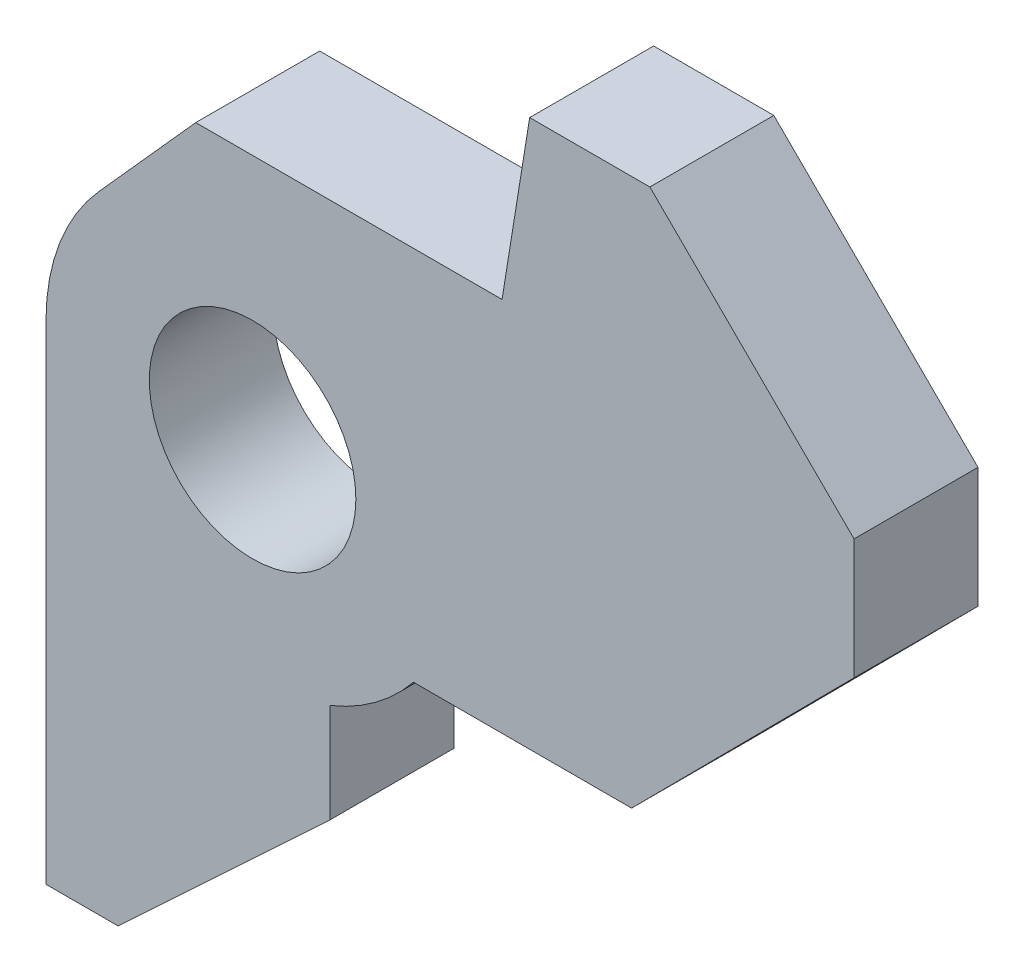
SolidWorks part; units mm, degrees
ref_plane "정면" through (0, 0, 0) normal (0, 0, 1) x (1, 0, 0)
ref_plane "윗면" through (0, 0, 0) normal (0, 1, 0) x (1, 0, 0)
ref_plane "우측면" through (0, 0, 0) normal (1, 0, 0) x (0, 0, -1)
sketch "스케치1" plane through (0, 0, 0) normal (0, 0, 1) x (1, 0, 0)
  line L1 (6.0379, 5.9574) -> (6.7063, 10.1037)
  line L2 (6.7063, 10.1037) -> (9.6154, 10.1037)
  line L3 (9.6154, 10.1037) -> (14.5571, 5.198)
  line L4 (14.5571, 5.198) -> (14.5571, 2.2863)
  line L5 (14.5571, 2.2863) -> (9.173, -3.1374)
  line L6 (9.173, -3.1374) -> (3.8932, -3.1374)
  line L7 (1.8761, -4.6347) -> (1.8761, -7.0314)
  line L8 (-3.2535, -11.8209) -> (-5, -11.8209)
  line L9 (-5, -11.8209) -> (-5, 0)
  line L10 (-3.2535, -11.8209) -> (1.8761, -7.0314)
  line L11 (6.0379, 5.9574) -> (-1.3764, 5.9574)
  line L12 (-1.3764, 5.9574) -> (-3.7244, 3.336)
  circle A0 centre (0, 0) radius 2.5
  circle A1 centre (0, 0) radius 5
  dimension "D1" = 5
  dimension "D2" = 10
extrude "보스-돌출1" add sketch "스케치1" along normal blind 3
